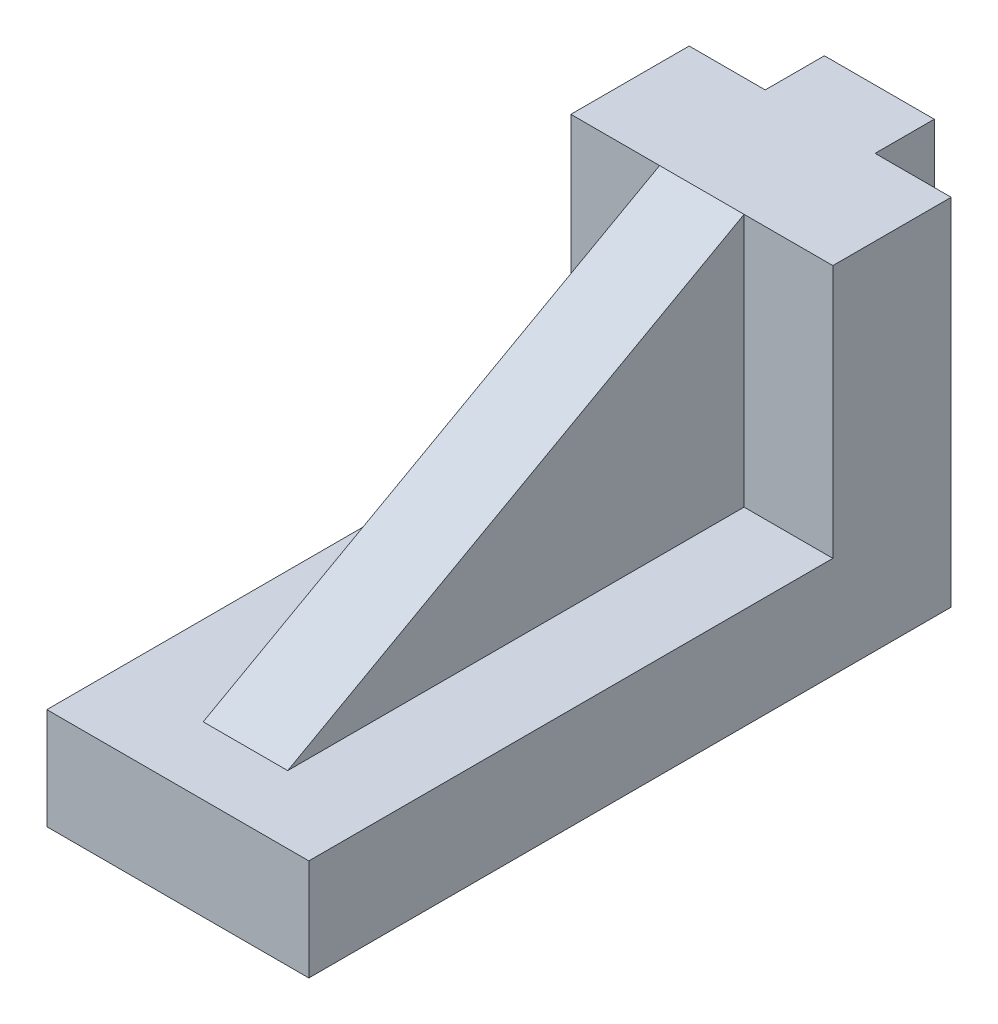
SolidWorks part; units mm, degrees
ref_plane "Alzado" through (0, 0, 0) normal (0, 0, 1) x (1, 0, 0)
ref_plane "Planta" through (0, 0, 0) normal (0, 1, 0) x (1, 0, 0)
ref_plane "Vista lateral" through (0, 0, 0) normal (1, 0, 0) x (0, 0, -1)
sketch "Croquis1" plane through (0, 0, 0) normal (1, 0, 0) x (0, 0, -1)
  line L1 (0, 0) -> (-76, 0)
  line L2 (0, 0) -> (0, 42)
  line L3 (0, 42) -> (-14, 42)
  line L4 (-76, 0) -> (-76, 12)
  line L7 (-76, 12) -> (-14, 12)
  line L8 (-14, 42) -> (-14, 12)
  dimension "D1" = 76
  dimension "D2" = 42
  dimension "D3" = 12
  dimension "D4" = 14
extrude "Saliente-Extruir1" add sketch "Croquis1" along normal mid plane 31
sketch "Croquis2" plane through (0, 42, 0) normal (0, 1, 0) x (1, 0, 0)
  line L0 (15.5, 0) -> (-15.5, 0) construction
  line L1 (-6.5, 0) -> (6.5, 0)
  line L2 (-6.5, 0) -> (-6.5, 7)
  line L3 (-6.5, 7) -> (6.5, 7)
  line L4 (6.5, 0) -> (6.5, 7)
  line L5 (15.5, -14) -> (-15.5, -14) construction
  point P6 (0, 7)
  dimension "D1" = 13
  dimension "D2" = 21
extrude "Saliente-Extruir2" add sketch "Croquis2" against normal up to surface (42 mm away) up to face at (0, 0, 38)
sketch "Croquis3" plane through (0, 0, 0) normal (1, 0, 0) x (0, 0, -1)
  line L0 (-68, 12) -> (-14, 42)
  line L1 (-14, 12) -> (-76, 12) construction
  line L2 (-76, 12) -> (-76, 0) construction
  dimension "D1" = 8
rib "Nervio1" sketch "Croquis3" sketch "Croquis3" thickness 10 extrusion direction parallel to sketch draft on no parameters "D1"=10
